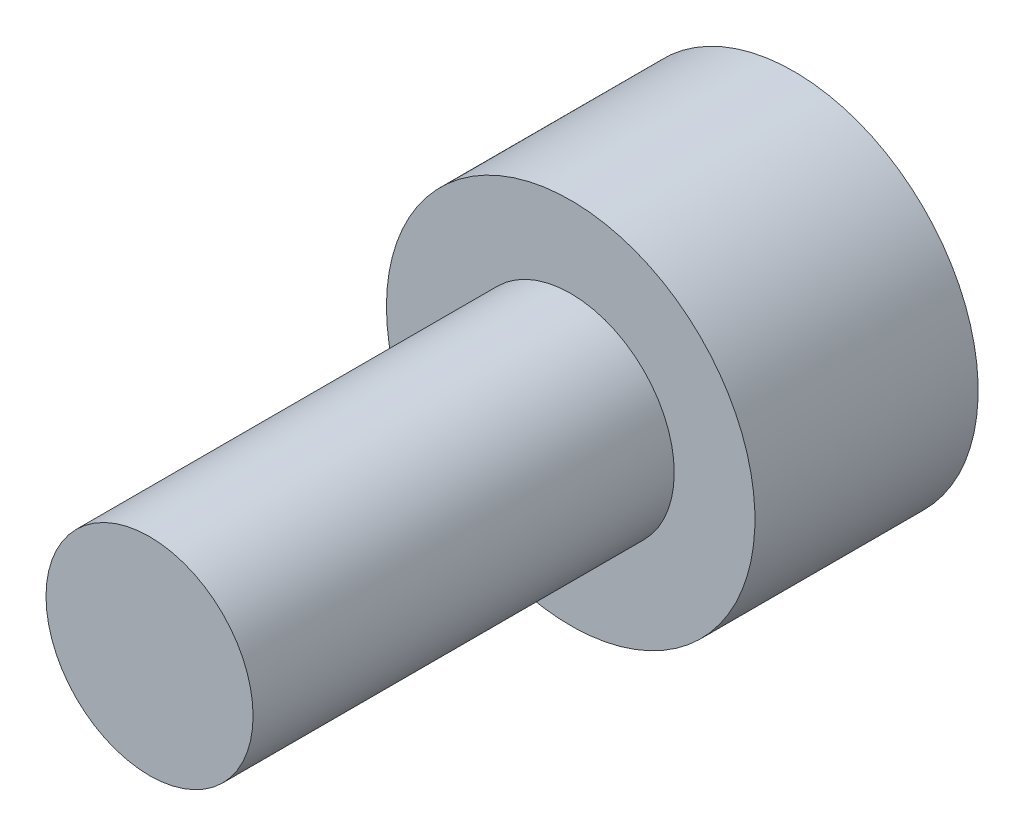
SolidWorks part; units mm, degrees
ref_plane "Front Plane" through (0, 0, 0) normal (0, 0, 1) x (1, 0, 0)
ref_plane "Top Plane" through (0, 0, 0) normal (0, 1, 0) x (1, 0, 0)
ref_plane "Right Plane" through (0, 0, 0) normal (1, 0, 0) x (0, 0, -1)
sketch "Sketch1" plane through (0, 0, 0) normal (0, 0, 1) x (1, 0, 0)
  circle A0 centre (0, 0) radius 2.625
  dimension "D1" = 5.25
extrude "Boss-Extrude1" add sketch "Sketch1" along normal blind 3.18 contours A0
sketch "Sketch2" plane through (0, 0, 3.18) normal (0, 0, 1) x (1, 0, 0)
  circle A0 centre (0, 0) radius 1.475
  dimension "D1" = 2.95
extrude "Boss-Extrude2" add sketch "Sketch2" along normal blind 6
